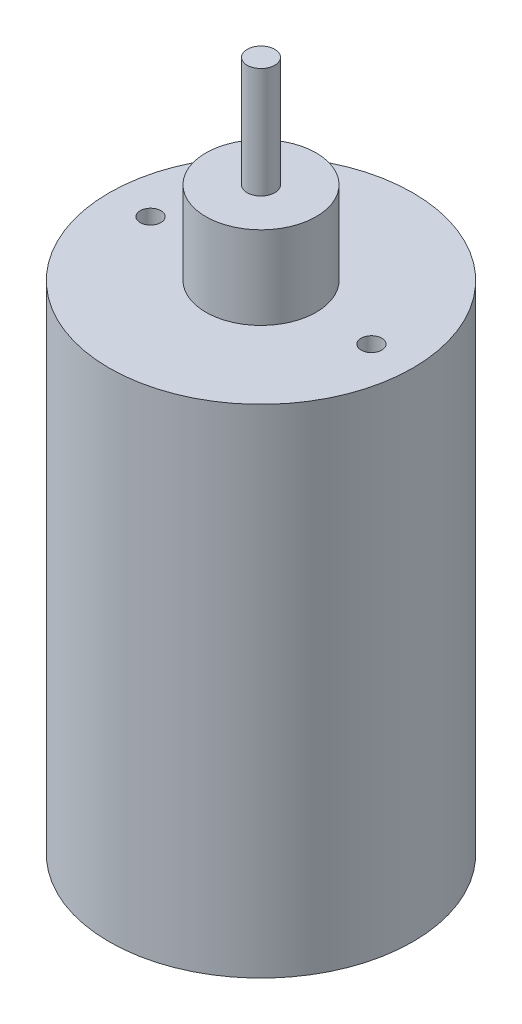
SolidWorks part; units mm, degrees
ref_plane "Front Plane" through (0, 0, 0) normal (0, 0, 1) x (1, 0, 0)
ref_plane "Top Plane" through (0, 0, 0) normal (0, 1, 0) x (1, 0, 0)
ref_plane "Right Plane" through (0, 0, 0) normal (1, 0, 0) x (0, 0, -1)
sketch "Sketch1" plane through (0, 0, 0) normal (0, 1, 0) x (1, 0, 0)
  circle A0 centre (0, 0) radius 17.4625
  dimension "D1" = 34.925
extrude "Boss-Extrude1" add sketch "Sketch1" along normal blind 57.15
sketch "Sketch2" plane through (0, 57.15, 0) normal (0, 1, 0) x (1, 0, 0)
  circle A0 centre (0, 0) radius 6.35
  dimension "D1" = 12.7
extrude "Boss-Extrude2" add sketch "Sketch2" along normal blind 9.525
sketch "Sketch3" plane through (0, 66.675, 0) normal (0, 1, 0) x (1, 0, 0)
  circle A0 centre (0, 0) radius 1.5875
  dimension "D1" = 3.175
extrude "Boss-Extrude3" add sketch "Sketch3" along normal blind 12.7
sketch "Sketch4" plane through (0, 57.15, 0) normal (0, 1, 0) x (1, 0, 0)
  line L0 (-17.4625, 0) -> (17.4625, 0) construction
  circle A0 centre (0, 0) radius 17.4625 construction
  circle A1 centre (12.7, 0) radius 1.1906
  circle A2 centre (-12.7, 0) radius 1.1906
  dimension "D3" = 2.3813
  dimension "D4" = 2.3813
  dimension "D1" = 12.7
  dimension "D2" = 12.7
extrude "Cut-Extrude1" cut sketch "Sketch4" against normal blind 12.7
